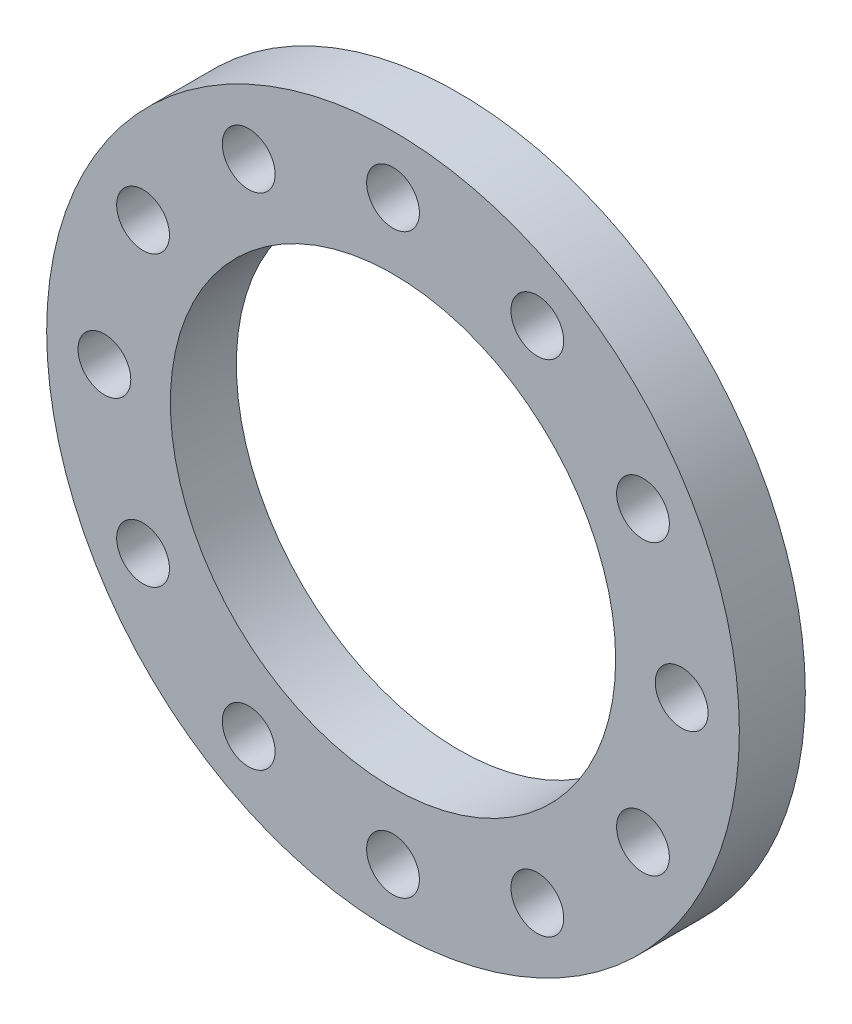
SolidWorks part; units mm, degrees
material "Thornel Mat VMA"
ref_plane "前视基准面" through (0, 0, 0) normal (0, 0, 1) x (1, 0, 0)
ref_plane "上视基准面" through (0, 0, 0) normal (0, 1, 0) x (1, 0, 0)
ref_plane "右视基准面" through (0, 0, 0) normal (1, 0, 0) x (0, 0, -1)
sketch "草图1" plane through (0, 0, 0) normal (0, 0, 1) x (1, 0, 0)
  line L0 (0, 0) -> (17.5, 0) construction
  circle A0 centre (0, 0) radius 21
  circle A1 centre (0, 0) radius 13.5
  circle A2 centre (0, 0) radius 17.5 construction
  circle A3 centre (0, 17.5) radius 1.6
  circle A4 centre (17.5, 0) radius 1.6
  circle A5 centre (0, -17.5) radius 1.6
  circle A6 centre (-17.5, 0) radius 1.6
  circle A7 centre (15.1554, -8.75) radius 1.6
  circle A8 centre (8.75, 15.1554) radius 1.6
  circle A9 centre (-15.1554, 8.75) radius 1.6
  circle A10 centre (-8.75, -15.1554) radius 1.6
  circle A11 centre (-15.1554, -8.75) radius 1.6
  circle A12 centre (8.75, -15.1554) radius 1.6
  circle A13 centre (15.1554, 8.75) radius 1.6
  circle A14 centre (-8.75, 15.1554) radius 1.6
  dimension "D1" = 42
  dimension "D2" = 27
  dimension "D3" = 35
  dimension "D4" = 3.2
  dimension "D6" = 17.5
  dimension "D5" = 3
extrude "凸台-拉伸1" add sketch "草图1" along normal blind 4
